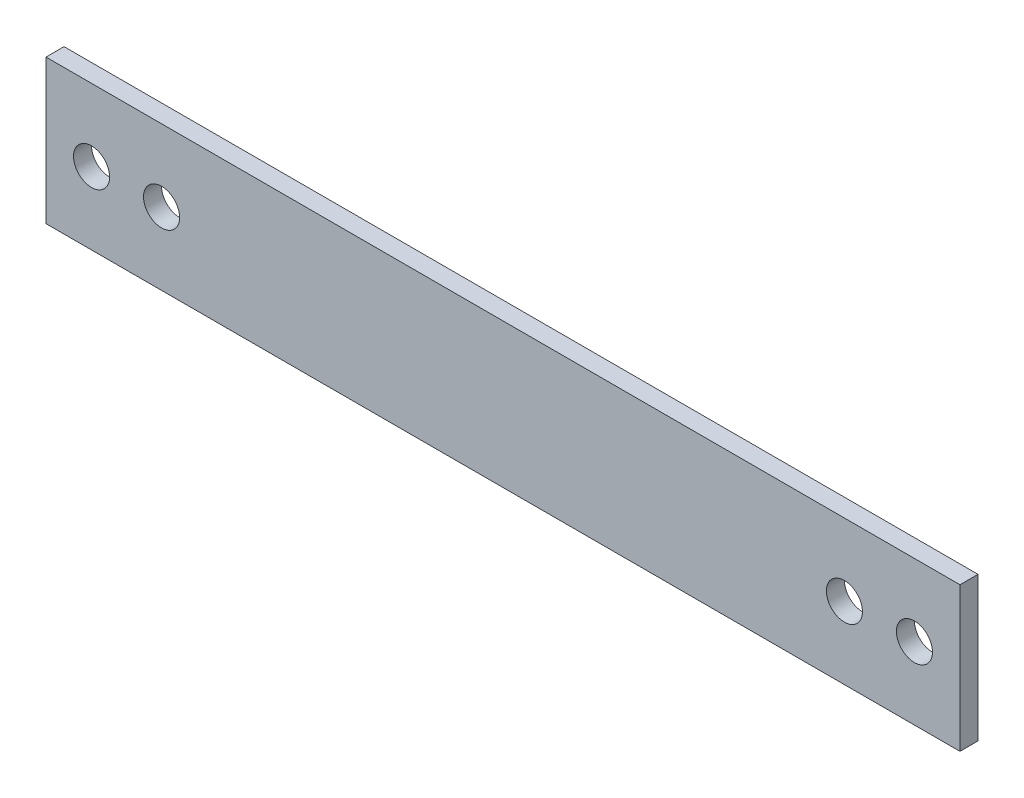
SolidWorks part; units mm, degrees
ref_plane "Front Plane" through (0, 0, 0) normal (0, 0, 1) x (1, 0, 0)
ref_plane "Top Plane" through (0, 0, 0) normal (0, 1, 0) x (1, 0, 0)
ref_plane "Right Plane" through (0, 0, 0) normal (1, 0, 0) x (0, 0, -1)
sketch "Sketch1" plane through (0, 0, 0) normal (0, 0, 1) x (1, 0, 0)
  line L1 (-120.65, -19.05) -> (120.65, -19.05)
  line L2 (-120.65, -19.05) -> (-120.65, 19.05)
  line L3 (-120.65, 19.05) -> (120.65, 19.05)
  line L4 (120.65, -19.05) -> (120.65, 19.05)
  line L5 (0, 19.05) -> (0, -19.05) construction
  line L6 (-120.65, 0) -> (120.65, 0) construction
  circle A0 centre (-108.6255, 0) radius 4.7625
  circle A1 centre (-90.143, 0) radius 4.7625
  circle A2 centre (90.143, 0) radius 4.7625
  circle A3 centre (108.6255, 0) radius 4.7625
  point P0 (0, 0)
  dimension "D3" = 9.525
  dimension "D1" = 38.1
  dimension "D2" = 241.3
extrude "Boss-Extrude1" add sketch "Sketch1" along normal blind 4.7625
